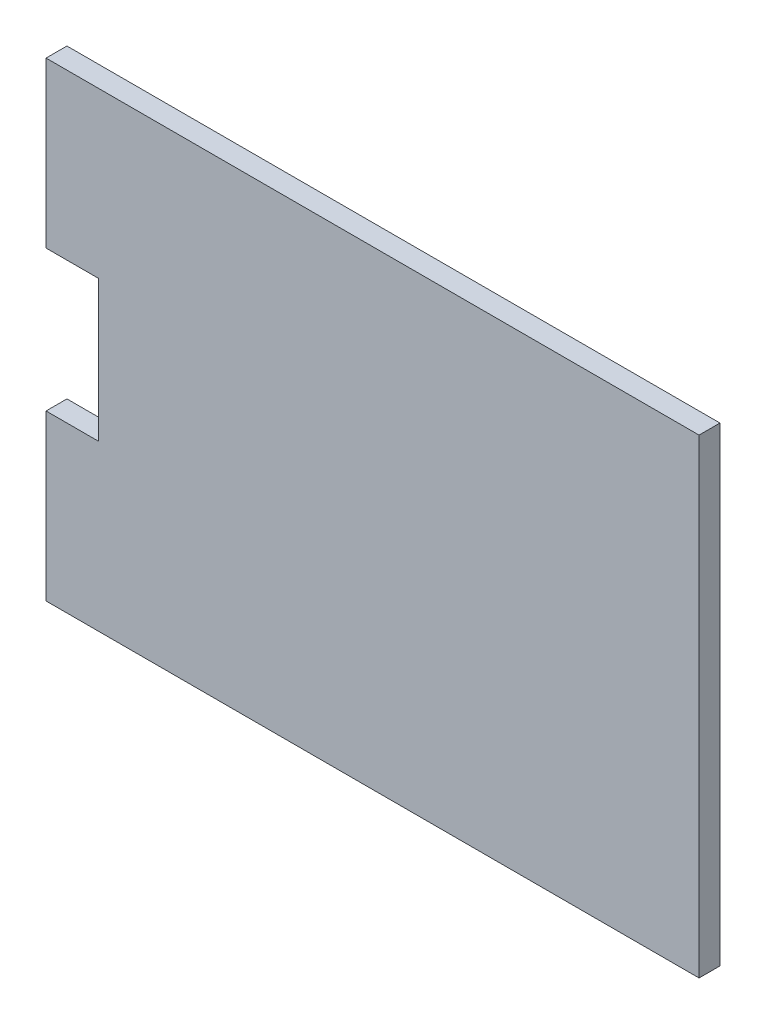
SolidWorks part; units mm, degrees
ref_plane "前视基准面" through (0, 0, 0) normal (0, 0, 1) x (1, 0, 0)
ref_plane "上视基准面" through (0, 0, 0) normal (0, 1, 0) x (1, 0, 0)
ref_plane "右视基准面" through (0, 0, 0) normal (1, 0, 0) x (0, 0, -1)
sketch "草图1" plane through (0, 0, 0) normal (0, 0, 1) x (1, 0, 0)
  line L1 (-127.6583, 89.0868) -> (122.3417, 89.0868)
  line L2 (-127.6583, 89.0868) -> (-127.6583, -90.9132)
  line L3 (-127.6583, -90.9132) -> (122.3417, -90.9132)
  line L4 (122.3417, 89.0868) -> (122.3417, -90.9132)
  dimension "D1" = 250
  dimension "D2" = 180
extrude "凸台-拉伸1" add sketch "草图1" along normal blind 8
sketch "草图2" plane through (0, 0, 8) normal (0, 0, 1) x (1, 0, 0)
  line L0 (-127.6583, 89.0868) -> (-127.6583, -90.9132) construction
  line L1 (-127.6583, 26.0868) -> (-107.6583, 26.0868)
  line L2 (-127.6583, 26.0868) -> (-127.6583, -27.9132)
  line L3 (-127.6583, -27.9132) -> (-107.6583, -27.9132)
  line L4 (-107.6583, 26.0868) -> (-107.6583, -27.9132)
  line L5 (122.3417, 89.0868) -> (-127.6583, 89.0868) construction
  dimension "D1" = 20
  dimension "D2" = 54
  dimension "D3" = 63
extrude "切除-拉伸1" cut sketch "草图2" against normal through all
